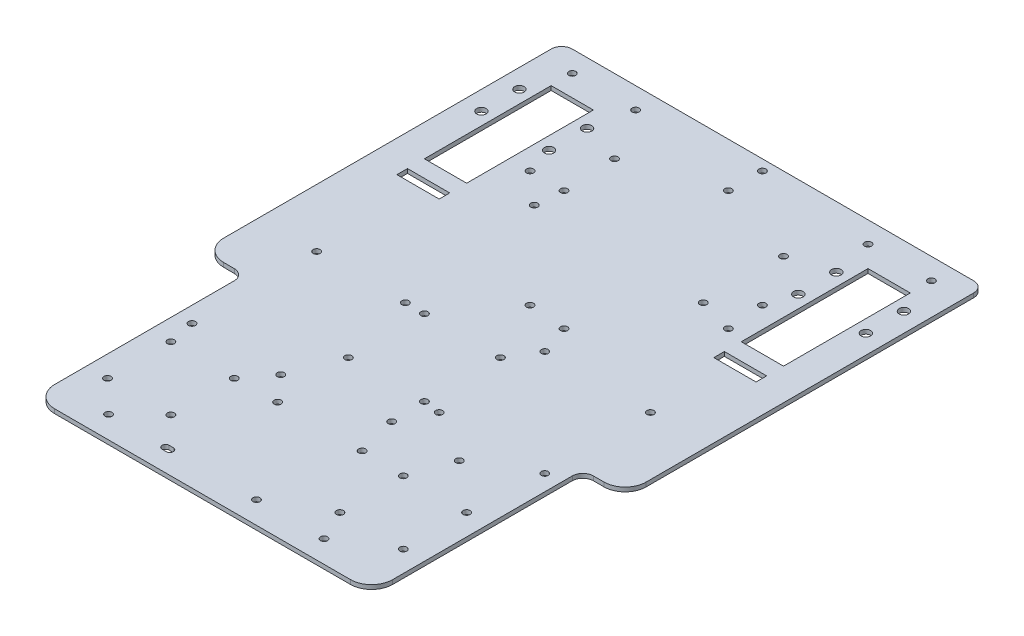
SolidWorks part; units mm, degrees
ref_plane "前视基准面" through (0, 0, 0) normal (0, 0, 1) x (1, 0, 0)
ref_plane "上视基准面" through (0, 0, 0) normal (0, 1, 0) x (1, 0, 0)
ref_plane "右视基准面" through (0, 0, 0) normal (1, 0, 0) x (0, 0, -1)
other "Configuration Table"
sketch "草图1" plane through (0, 0, 0) normal (0, 1, 0) x (1, 0, 0)
  line L0 (85, 50) -> (90, 50)
  line L2 (-80, 45) -> (-80, -40)
  line L3 (-70, -50) -> (70, -50)
  line L4 (80, 45) -> (80, -40)
  line L5 (-95, 220) -> (-45, 220)
  line L6 (0, -865) -> (0, -50) construction
  line L7 (-95, 220) -> (95, 220)
  line L8 (-100, 215) -> (-100, 60)
  line L9 (-90, 50) -> (-85, 50)
  line L10 (100, 215) -> (100, 60)
  line L11 (-55, -1010) -> (-55, -10) construction
  line L12 (-55, 220) -> (-55, 48990) construction
  line L15 (2, -50) -> (60, -50)
  line L55 (-85, 200) -> (-45, 200)
  line L56 (0, 216.65) -> (0, 49135) construction
  line L58 (85, 200) -> (65, 200)
  line L59 (-28, -39.5) -> (-26, -39.5) construction
  line L66 (-28, -37.85) -> (-26, -37.85)
  line L67 (-28, -41.15) -> (-26, -41.15)
  line L70 (-37.2409, 160) -> (38.8909, 160) construction
  line L76 (65, 132) -> (85, 132)
  line L89 (-85, 200) -> (-65, 200)
  line L90 (-85, 200) -> (-85, 140)
  line L91 (-85, 140) -> (-65, 140)
  line L92 (-65, 200) -> (-65, 140)
  line L93 (-65, 127) -> (-85, 127)
  line L94 (-65, 127) -> (-65, 132)
  line L95 (-65, 132) -> (-85, 132)
  line L96 (-85, 127) -> (-85, 132)
  line L101 (85, 127) -> (85, 132)
  line L102 (65, 127) -> (85, 127)
  line L103 (65, 127) -> (65, 132)
  line L104 (85, 140) -> (65, 140)
  line L105 (65, 200) -> (65, 140)
  line L106 (85, 200) -> (85, 140)
  line L108 (0, 198.8909) -> (0, 213.35) construction
  arc A0 (-80, 45) -> (-85, 50) centre (-85, 45) ccw
  arc A1 (80, 45) -> (85, 50) centre (85, 45) cw
  arc A2 (100, 60) -> (90, 50) centre (90, 60) cw
  arc A3 (-100, 60) -> (-90, 50) centre (-90, 60) ccw
  circle A13 centre (47, -39.5) radius 1.65
  circle A15 centre (-40, 5) radius 1.65
  circle A16 centre (-40, -25) radius 1.65
  circle A17 centre (-70, -25) radius 1.65
  circle A18 centre (-70, 5) radius 1.65
  circle A19 centre (70, 5) radius 1.65
  circle A20 centre (70, -25) radius 1.65
  circle A21 centre (40, -25) radius 1.65
  circle A22 centre (40, 5) radius 1.65
  circle A23 centre (47, 24.5) radius 1.65
  circle A24 centre (15, 24.5) radius 1.65
  circle A25 centre (15, -39.5) radius 1.65
  circle A26 centre (-30.5, 76.5) radius 1.65
  circle A27 centre (-72.5, 76.5) radius 1.65
  circle A28 centre (-30.5, 17.5) radius 1.65
  circle A29 centre (-72.5, 17.5) radius 1.65
  circle A30 centre (22.5, 89.5) radius 1.65
  circle A31 centre (72.5, 89.5) radius 1.65
  circle A32 centre (72.5, 39.5) radius 1.65
  circle A33 centre (22.5, 39.5) radius 1.65
  circle A36 centre (0, 215) radius 1.65
  circle A37 centre (-85, 210) radius 1.65
  circle A38 centre (-55, 210) radius 1.65
  circle A39 centre (85, 210) radius 1.65
  circle A40 centre (55, 210) radius 1.65
  circle A41 centre (55, 160) radius 1.65
  circle A42 centre (0, 105) radius 1.65
  circle A43 centre (-55, 160) radius 1.65
  circle A48 centre (-55, -39.5) radius 1.65
  circle A49 centre (-20, 5.5) radius 1.65
  circle A50 centre (20, 5.5) radius 1.65
  arc A52 (-28, -37.85) -> (-28, -41.15) centre (-28, -39.5) ccw
  arc A53 (-26, -41.15) -> (-26, -37.85) centre (-26, -39.5) ccw
  circle A56 centre (0, 198.8909) radius 1.65
  circle A57 centre (-38.8909, 160) radius 1.65
  circle A58 centre (17.6777, 103.4315) radius 1.65
  circle A59 centre (56.5685, 142.3223) radius 1.65
  circle A60 centre (-21.5, 76.5) radius 1.65
  circle A61 centre (14.5, 76.5) radius 1.65
  circle A62 centre (14.5, 40.5) radius 1.65
  circle A63 centre (-21.5, 40.5) radius 1.65
  circle A64 centre (-91, 191) radius 2.25
  circle A65 centre (-91, 173) radius 2.25
  circle A66 centre (-59, 191) radius 2.25
  circle A67 centre (-59, 173) radius 2.25
  circle A68 centre (91, 191) radius 2.25
  circle A69 centre (59, 191) radius 2.25
  circle A70 centre (59, 173) radius 2.25
  circle A71 centre (91, 173) radius 2.25
  circle A72 centre (-40, 185) radius 1.65
  circle A73 centre (-40, 147) radius 1.65
  circle A74 centre (40, 147) radius 1.65
  circle A75 centre (40, 185) radius 1.65
  arc A76 (-70, -50) -> (-80, -40) centre (-70, -40) cw
  arc A77 (70, -50) -> (80, -40) centre (70, -40) ccw
  arc A78 (-95, 220) -> (-100, 215) centre (-95, 215) ccw
  arc A79 (100, 215) -> (95, 220) centre (95, 215) ccw
  point P0 (0, 0)
  point P6 (0, 135)
  point P15 (80, 50)
  point P18 (100, 50)
  point P21 (31, -7.5)
  point P41 (-51.5, 47)
  point P48 (-51.5, 47)
  point P53 (80, 2.5)
  point P54 (47.5, 64.5)
  point P59 (31, -7.5)
  point P66 (47.5, 64.5)
  point P85 (-177.567, 188.7139)
  point P130 (-3.5, 58.5)
  point P138 (-27, -39.5)
  point P145 (-3.5, 58.5)
  point P201 (-96.7046, 175.5577)
  point P202 (-103.6078, 179.5024)
  point P207 (-80, -50)
  point P210 (80, -50)
  point P213 (-100, 220)
  point P216 (100, 220)
  dimension "D7" = 5
  dimension "D8" = 5
  dimension "D9" = 10
  dimension "D10" = 10
  dimension "D15" = 100
  dimension "D16" = 25
  dimension "D33" = 3.3
  dimension "D34" = 3.3
  dimension "D13" = 3.3
  dimension "D19" = 3.3
  dimension "D36" = 3.3
  dimension "D40" = 3.3
  dimension "D41" = 3.3
  dimension "D42" = 3.3
  dimension "D43" = 3.3
  dimension "D44" = 3.3
  dimension "D49" = 3.3
  dimension "D53" = 3.3
  dimension "D54" = 3.3
  dimension "D64" = 3.3
  dimension "D70" = 3.3
  dimension "D71" = 3.3
  dimension "D79" = 3.3
  dimension "D80" = 3.3
  dimension "D81" = 3.3
  dimension "D82" = 3.3
  dimension "D89" = 3.3
  dimension "D95" = 4.5
  dimension "D96" = 4.5
  dimension "D97" = 4.5
  dimension "D98" = 4.5
  dimension "D111" = 3.3
  dimension "D112" = 3.3
  dimension "D117" = 10
  dimension "D118" = 10
  dimension "D119" = 5
  dimension "D120" = 5
  dimension "D1" = 160
  dimension "D2" = 100
  dimension "D3" = 170
  dimension "D4" = 200
  dimension "D5" = 0
  dimension "D6" = 135
  dimension "D11" = 50
  dimension "D12" = 25
  dimension "D14" = 15
  dimension "D18" = 80
  dimension "D31" = 64
  dimension "D32" = 32
  dimension "D17" = 15
  dimension "D37" = 59
  dimension "D38" = 42
  dimension "D55" = 10
  dimension "D56" = 10
  dimension "D57" = 30
  dimension "D60" = 55
  dimension "D65" = 10.5
  dimension "D66" = 60
  dimension "D67" = 60
  dimension "D68" = 40
  dimension "D69" = 45
  dimension "D72" = 2
  dimension "D73" = 1.65
  dimension "D74" = 28
  dimension "D75" = 10.5
  dimension "D63" = 25
  dimension "D76" = 55
  dimension "D77" = 55
  dimension "D91" = 20
  dimension "D92" = 15
  dimension "D93" = 0
  dimension "D94" = 60
  dimension "D99" = 18
  dimension "D100" = 18
  dimension "D101" = 6
  dimension "D102" = 6
  dimension "D103" = 9
  dimension "D104" = 0
  dimension "D105" = 6
  dimension "D106" = 6
  dimension "D107" = 5
  dimension "D108" = 68
  dimension "D109" = 15
  dimension "D110" = 20
  dimension "D113" = 25
  dimension "D114" = 38
  dimension "D115" = 40
  dimension "D116" = 40
  dimension "D35" = 4
  dimension "D45" = 4
  dimension "D59" = 4
  dimension "D90" = 4
extrude "凸台-拉伸1" add sketch "草图1" along normal blind 2
